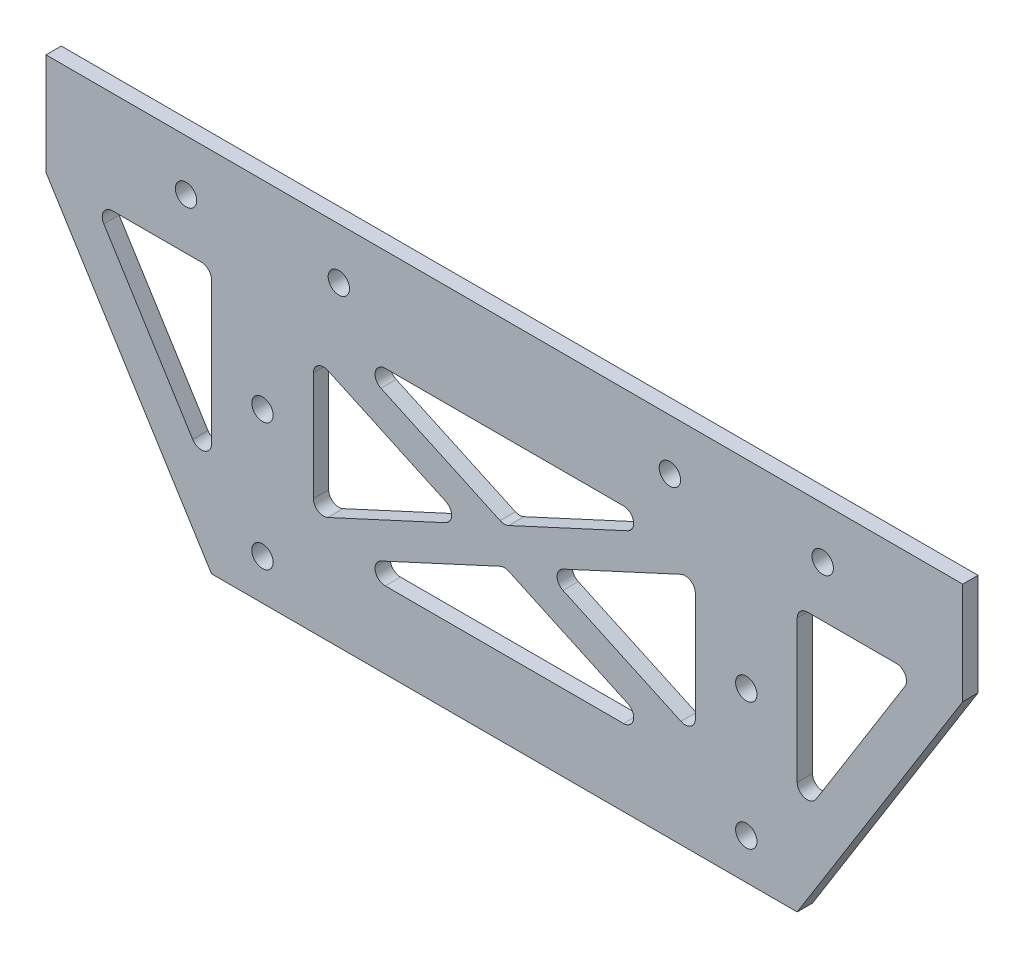
SolidWorks part; units mm, degrees
material "环氧树脂FR-4"
ref_plane "前视基准面" through (0, 0, 0) normal (0, 0, 1) x (1, 0, 0)
ref_plane "上视基准面" through (0, 0, 0) normal (0, 1, 0) x (1, 0, 0)
ref_plane "右视基准面" through (0, 0, 0) normal (1, 0, 0) x (0, 0, -1)
sketch "草图1" plane through (0, 0, 0) normal (0, 0, 1) x (1, 0, 0)
  line L1 (-90, 36) -> (90, 36)
  line L2 (-90, 36) -> (-90, -36)
  line L3 (-90, -36) -> (90, -36)
  line L4 (90, 36) -> (90, -36)
  line L5 (-90, 36) -> (90, -36) construction
  line L6 (-90, -36) -> (90, 36) construction
  point P0 (0, 0)
  dimension "D1" = 72
  dimension "D2" = 180
extrude "凸台-拉伸1" add sketch "草图1" along normal blind 3
sketch "草图2" plane through (0, 0, 3) normal (0, 0, 1) x (1, 0, 0)
  line L0 (90, 36) -> (-90, 36) construction
  line L1 (0, -55) -> (0, 55) construction
  point P0 (-32.5, 26)
  point P1 (-62.5, 26)
  point P7 (62.5, 26)
  point P8 (32.5, 26)
  point P9 (-47.5, -3)
  point P10 (-47.5, -28)
  point P11 (47.5, -28)
  point P12 (47.5, -3)
  dimension "D1" = 10
  dimension "D2" = 32.5
  dimension "D3" = 10
  dimension "D4" = 30
  dimension "D5" = 47.5
  dimension "D6" = 29
  dimension "D7" = 25
  dimension "D8" = 47.5
hole_wizard "Ø4.2 (4.2) 直径孔1" positions "3D草图1" profile "草图3" hole size "Ø4.2" standard "GB" end condition through all
sketch3d "3D草图1"
  point P0 (-62.5, 26, 3)
  point P3 (-32.5, 26, 3)
  point P6 (-47.5, -3, 3)
  point P9 (-47.5, -28, 3)
  point P12 (47.5, -28, 3)
  point P15 (47.5, -3, 3)
  point P18 (62.5, 26, 3)
  point P21 (32.5, 26, 3)
sketch "草图3" plane through (-62.5, 26, 3) normal (1, 0, 0) x (0, -1, 0)
  line L0 (0, 0) -> (0, 3)
  line L1 (0, 3) -> (2.1, 3)
  line L2 (2.1, 3) -> (2.1, 0)
  line L5 (2.1, 0) -> (0, 0)
  line L11 (0, -6.35) -> (0, 107.95) construction
  dimension "通孔孔直径" = 4.2
  dimension "通孔孔深度" = 3
sketch "草图8" plane through (0, 0, 0) normal (0, 0, -1) x (-1, 0, 0)
  line L0 (-90, 36) -> (90, 36) construction
  line L1 (-90, -36) -> (-90, 36) construction
  line L4 (-90, 16) -> (-57.5, -36)
  line L5 (90, -36) -> (-90, -36) construction
  line L6 (-57.5, -36) -> (-90, -36)
  line L7 (-90, -36) -> (-90, 16)
  line L8 (0, 55) -> (0, -55) construction
  line L9 (90, -36) -> (90, 16)
  line L10 (57.5, -36) -> (90, -36)
  line L11 (90, 16) -> (57.5, -36)
  dimension "D1" = 0
  dimension "D2" = 20
  dimension "D3" = 10
extrude "切除-拉伸2" cut sketch "草图8" against normal through all
sketch "草图6" plane through (0, 0, 0) normal (0, 0, -1) x (-1, 0, 0)
  line L0 (0, 55) -> (0, -55) construction
  line L13 (57.5, 14) -> (57.5, -13.932)
  line L14 (76.9575, 16) -> (59.5, 16)
  line L15 (61.196, -14.992) -> (78.6535, 12.94)
  line L24 (-76.9575, 16) -> (-59.5, 16)
  line L25 (-57.5, 14) -> (-57.5, -13.932)
  line L26 (-61.196, -14.992) -> (-78.6535, 12.94)
  line L31 (-57.5, -36) -> (-90, 16) construction
  line L32 (-23.3941, 16) -> (23.3941, 16)
  line L33 (-37.5, 8.1819) -> (-37.5, -13.1819)
  line L34 (-23.3941, -21) -> (23.3941, -21)
  line L35 (37.5, 8.1819) -> (37.5, -13.1819)
  line L36 (11.5178, -4.3159) -> (34.6619, -14.9978)
  line L37 (-90, 36) -> (90, 36) construction
  line L38 (-34.6619, 9.9978) -> (-11.5178, -0.6841)
  line L39 (-24.2322, 12.1841) -> (-0.8381, 1.3868)
  line L40 (-24.2322, -17.1841) -> (-0.8381, -6.3868)
  line L41 (-34.6619, -14.9978) -> (-11.5178, -4.3159)
  line L42 (0.8381, -6.3868) -> (24.2322, -17.1841)
  line L43 (0.8381, 1.3868) -> (24.2322, 12.1841)
  line L45 (11.5178, -0.6841) -> (34.6619, 9.9978)
  line L46 (57.5, -36) -> (-57.5, -36) construction
  arc A0 (76.9575, 16) -> (78.6535, 12.94) centre (76.9575, 14) cw
  arc A1 (57.5, 14) -> (59.5, 16) centre (59.5, 14) cw
  arc A2 (57.5, -13.932) -> (61.196, -14.992) centre (59.5, -13.932) ccw
  arc A3 (24.2322, -17.1841) -> (23.3941, -21) centre (23.3941, -19) cw
  arc A4 (-23.3941, -21) -> (-24.2322, -17.1841) centre (-23.3941, -19) cw
  arc A5 (0.8381, -6.3868) -> (-0.8381, -6.3868) centre (0, -8.2027) ccw
  arc A6 (37.5, 8.1819) -> (34.6619, 9.9978) centre (35.5, 8.1819) ccw
  arc A7 (37.5, -13.1819) -> (34.6619, -14.9978) centre (35.5, -13.1819) cw
  arc A8 (11.5178, -0.6841) -> (11.5178, -4.3159) centre (12.3559, -2.5) ccw
  arc A9 (23.3941, 16) -> (24.2322, 12.1841) centre (23.3941, 14) cw
  arc A10 (0.8381, 1.3868) -> (-0.8381, 1.3868) centre (0, 3.2027) cw
  arc A11 (-24.2322, 12.1841) -> (-23.3941, 16) centre (-23.3941, 14) cw
  arc A12 (-11.5178, -0.6841) -> (-11.5178, -4.3159) centre (-12.3559, -2.5) cw
  arc A13 (-34.6619, -14.9978) -> (-37.5, -13.1819) centre (-35.5, -13.1819) cw
  arc A14 (-37.5, 8.1819) -> (-34.6619, 9.9978) centre (-35.5, 8.1819) cw
  arc A15 (-59.5, 16) -> (-57.5, 14) centre (-59.5, 14) cw
  arc A16 (-57.5, -13.932) -> (-61.196, -14.992) centre (-59.5, -13.932) cw
  arc A17 (-76.9575, 16) -> (-78.6535, 12.94) centre (-76.9575, 14) ccw
  point P3 (-39.9524, 16)
  point P4 (39.8382, -23.5446)
  point P5 (-39.9524, -23.5446)
  point P6 (39.8382, 16)
  point P9 (-41.2845, 13.312)
  point P10 (38.506, -26.2326)
  point P13 (-38.6202, -26.2326)
  point P14 (41.1704, 13.312)
  point P15 (-41.2845, -20.8566)
  point P16 (38.506, 18.688)
  point P23 (-55.7305, 13.5774)
  point P24 (117.9492, 11.9624)
  point P25 (60.4492, -30.0376)
  point P29 (-113.2305, -28.4226)
  point P48 (80.566, 16)
  point P51 (57.5, 16)
  point P54 (57.5, -20.9056)
  point P57 (32.5, -21)
  point P60 (-32.5, -21)
  point P63 (0, -6)
  point P70 (7.5833, -2.5)
  point P73 (32.5, 16)
  point P76 (0, 1)
  point P79 (-32.5, 16)
  point P88 (-57.5, 16)
  point P91 (-57.5, -20.9056)
  point P94 (-80.566, 16)
  dimension "D15" = 2
  dimension "D1" = 10
  dimension "D2" = 8
  dimension "D3" = 20
  dimension "D4" = 10
  dimension "D5" = 10
  dimension "D6" = 15
  dimension "D7" = 15
  dimension "D8" = 15
  dimension "D9" = 0
  dimension "D10" = 6
  dimension "D11" = 0
  dimension "D12" = 0
  dimension "D13" = 0
  dimension "D14" = 0
extrude "切除-拉伸3" cut sketch "草图6" against normal through all
